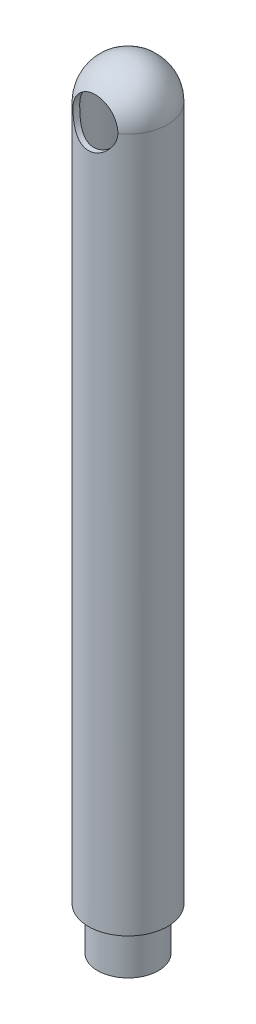
SolidWorks part; units mm, degrees
material "Chrome Stainless Steel"
ref_plane "Plano frontal" through (0, 0, 0) normal (0, 0, 1) x (1, 0, 0)
ref_plane "Plano superior" through (0, 0, 0) normal (0, 1, 0) x (1, 0, 0)
ref_plane "Plano direito" through (0, 0, 0) normal (1, 0, 0) x (0, 0, -1)
sketch "Sketch1" plane through (0, 0, 0) normal (0, 0, 1) x (1, 0, 0)
  line L0 (0, 0) -> (0, 893.401) construction
  line L1 (28.5, 0) -> (28.5, 40)
  line L2 (28.5, 40) -> (37, 40)
  line L3 (37, 40) -> (37, 689)
  line L4 (23.5, 0) -> (23.5, 45)
  line L5 (23.5, 45) -> (32, 45)
  line L6 (32, 45) -> (32, 821)
  line L7 (28.5, 0) -> (23.5, 0)
  line L8 (32, 45) -> (32, 689) construction
  line L9 (0, 726) -> (0, 721)
  arc A0 (37, 689) -> (0, 726) centre (0, 689) ccw
  arc A1 (32, 689) -> (0, 721) centre (0, 689) ccw
  dimension "D6" = 37
  dimension "D1" = 57
  dimension "D2" = 40
  dimension "D3" = 74
  dimension "D5" = 649
  dimension "D4" = 5
  dimension "D7" = 5
revolve "Revolve1" add sketch "Sketch1" angle 360 about L0
sketch "Sketch2" plane through (0, 0, 0) normal (0, 0, 1) x (1, 0, 0)
  line L0 (37, 689) -> (-37, 689) construction
  circle A0 centre (0, 689) radius 21
  dimension "D1" = 42
extrude "Cut-Extrude1" cut sketch "Sketch2" against normal through all both and the other way through all
